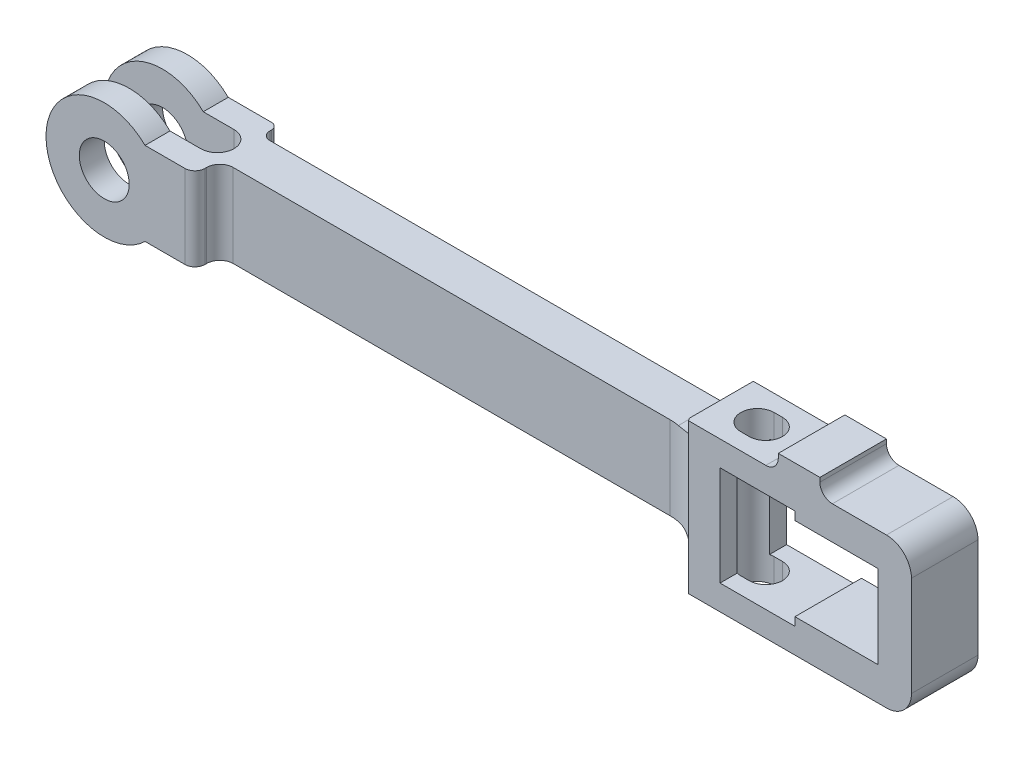
SolidWorks part; units mm, degrees
ref_plane "Plan de face" through (0, 0, 0) normal (0, 0, 1) x (1, 0, 0)
ref_plane "Plan de dessus" through (0, 0, 0) normal (0, 1, 0) x (1, 0, 0)
ref_plane "Plan de droite" through (0, 0, 0) normal (1, 0, 0) x (0, 0, -1)
sketch "Esquisse1" plane through (0, 0, 0) normal (0, 0, 1) x (1, 0, 0)
  line L0 (-1000, 0) -> (49000, 0) construction
  line L1 (3.5, 2.5) -> (2.4495, 2.5)
  line L2 (3.5, -2.5) -> (33.05, -2.5)
  line L6 (3.5, -2.5) -> (2.4495, -2.5)
  line L7 (35, 4.45) -> (35, 4.5)
  line L8 (35, 4.5) -> (39.75, 4.5)
  line L9 (35, -4.45) -> (35, -4.5)
  line L10 (35, -4.5) -> (47, -4.5)
  line L11 (48.5, 3) -> (48.5, -3)
  line L12 (3.5, 2.5) -> (33.05, 2.5)
  line L13 (37, -3) -> (37, 3)
  line L14 (37, 2.5) -> (46.5, 2.5) construction
  line L15 (37, 2.5) -> (37, -2.5) construction
  line L16 (37, -2.5) -> (46.5, -2.5) construction
  line L17 (46.5, 2.5) -> (46.5, -2.5) construction
  line L18 (37, 3) -> (41.5, 3) construction
  line L19 (37, 3) -> (37, -3) construction
  line L20 (37, -3) -> (41.5, -3) construction
  line L21 (41.5, 3) -> (41.5, -3) construction
  line L22 (37, 3) -> (41.5, 3)
  line L23 (41.5, 3) -> (41.5, 2.5)
  line L24 (41.5, 2.5) -> (46.5, 2.5)
  line L25 (46.5, 2.5) -> (46.5, -2.5)
  line L26 (46.5, -2.5) -> (41.5, -2.5)
  line L27 (41.5, -2.5) -> (41.5, -3)
  line L28 (41.5, -3) -> (37, -3)
  line L29 (43.75, 4.5) -> (47, 4.5)
  line L31 (40.5, 5.25) -> (40.5, 5.5)
  line L32 (40.5, 5.5) -> (43, 5.5)
  line L33 (43, 5.25) -> (43, 5.5)
  circle A0 centre (0, 0) radius 1.5
  circle A1 centre (0, 0) radius 3.5
  arc A2 (35, -4.45) -> (33.05, -2.5) centre (33.05, -4.45) ccw
  arc A3 (35, 4.45) -> (33.05, 2.5) centre (33.05, 4.45) cw
  arc A4 (39.75, 4.5) -> (40.5, 5.25) centre (39.75, 5.25) ccw
  arc A5 (43.75, 4.5) -> (43, 5.25) centre (43.75, 5.25) cw
  arc A6 (48.5, 3) -> (47, 4.5) centre (47, 3) ccw
  arc A7 (48.5, -3) -> (47, -4.5) centre (47, -3) cw
  point P34 (43, 5.375)
  point P39 (43, 4.5)
  point P44 (48.5, -4.5)
  dimension "D1" = 3
  dimension "D2" = 7
  dimension "D5" = 1.95
  dimension "D21" = 0.75
  dimension "D23" = 0.75
  dimension "D24" = 1.5
  dimension "D25" = 1.5
  dimension "D3" = 2.5
  dimension "D4" = 37
  dimension "D6" = 46.5
  dimension "D7" = 1.0505
  dimension "D8" = 2.5
  dimension "D9" = 2.5
  dimension "D10" = 13.5
  dimension "D11" = 48.5
  dimension "D12" = 0.05
  dimension "D13" = 5
  dimension "D14" = 6
  dimension "D15" = 3
  dimension "D16" = 41.5
  dimension "D17" = 0
  dimension "D18" = 40.5
  dimension "D19" = 43
  dimension "D20" = 1
  dimension "D22" = 0.25
extrude "Boss.-Extru.1" add sketch "Esquisse1" along normal blind 5 contours A1 A0 | A7 L11 A6 L29 A5 L33 L32 L31 A4 L8 L7 A3 L12 L1 A1 L6 L2 A2 L9 L10 L27 L28 L13 L22 L23 L24 L25 L26
sketch "Esquisse2" plane through (0, 2.5, 0) normal (0, 1, 0) x (1, 0, 0)
  line L0 (-997.5505, -2.5) -> (49002.4495, -2.5) construction
  line L1 (2.4495, -5) -> (2.4495, 0) construction
  line L2 (0, -1000) -> (0, 49000) construction
  line L3 (-997.5505, -3.5) -> (49002.4495, -3.5) construction
  line L4 (3.7273, -3.499) -> (50003.7273, -3.499) construction
  line L5 (-1001.8476, -1) -> (48998.1524, -1) construction
  line L6 (5.9495, -1) -> (48.5, -1)
  line L7 (48.5, -5) -> (48.5, 0) construction
  line L8 (5.4495, -0.5) -> (5.4495, -0.4)
  line L9 (2.4495, 0) -> (33.05, 0) construction
  line L10 (2.4495, 0) -> (5.0495, 0)
  line L11 (-3.5, 0) -> (2.4495, 0)
  line L12 (-3.5, 0) -> (-3.5, -1.5)
  line L13 (-3.5, 0) -> (-3.5, -5) construction
  line L14 (-3.5, -5) -> (-3.5, -3.5)
  line L15 (-3.5, -1.5) -> (3.5, -1.5)
  line L16 (-3.5, -3.5) -> (3.5, -3.5)
  line L17 (2.4495, -5) -> (-3.5, -5)
  line L18 (2.4495, -5) -> (4.8495, -5)
  line L19 (2.4495, -5) -> (33.05, -5) construction
  line L20 (5.4495, -4.4) -> (5.4495, -4.3)
  line L21 (6.2495, -3.5) -> (32.5, -3.5)
  line L22 (32.5, -3.5) -> (32.5, -8.2558) construction
  line L23 (40.5, -5) -> (43, -5) construction
  line L24 (35.0981, -5) -> (48.5, -5)
  line L25 (48.5, -5) -> (48.5, -1)
  line L26 (-3.5, -1.5) -> (-3.5, -3.5)
  line L27 (4.8495, -5) -> (35.0981, -5)
  line L28 (5.0495, 0) -> (48.5, 0)
  line L29 (48.5, 0) -> (48.5, -1)
  line L30 (3.5, -3.5) -> (4.2951, -3.5)
  line L31 (4.2951, -1.5) -> (3.5, -1.5)
  arc A0 (5.9495, -1) -> (5.4495, -0.5) centre (5.9495, -0.5) cw
  arc A1 (5.4495, -0.4) -> (5.0495, 0) centre (5.0495, -0.4) ccw
  arc A3 (5.4495, -4.3) -> (6.2495, -3.5) centre (6.2495, -4.3) cw
  arc A4 (4.8495, -5) -> (5.4495, -4.4) centre (4.8495, -4.4) ccw
  arc A5 (32.5, -3.5) -> (35.0981, -5) centre (32.5, -6.5) cw
  arc A6 (4.2951, -3.5) -> (4.2951, -1.5) centre (4.2951, -2.5) ccw
  point P5 (2.4495, -2.5)
  point P28 (5.4495, 0)
  point P47 (5.4495, -3.5)
  point P50 (5.4495, -5)
  point P51 (32.5, -6.5)
  dimension "D6" = 0.5
  dimension "D7" = 0.4
  dimension "D9" = 1
  dimension "D12" = 0.8
  dimension "D13" = 0.6
  dimension "D1" = 2.5
  dimension "D2" = 1
  dimension "D3" = 1.5
  dimension "D4" = 1.5
  dimension "D5" = 3
  dimension "D8" = 7
  dimension "D10" = 5.4495
  dimension "D11" = 32.5
  dimension "D14" = 3
extrude "Enlèv. mat.-Extru.2" cut sketch "Esquisse2" against normal through all both and the other way through all
sketch "Esquisse3" plane through (0, 4.5, 0) normal (0, 1, 0) x (1, 0, 0)
  line L0 (37.7503, -3) -> (37.2503, -3) construction
  line L1 (37.7503, -4) -> (37.2503, -4)
  line L2 (37.7503, -2) -> (37.2503, -2)
  line L3 (35.0981, -5) -> (39.75, -5) construction
  line L4 (35, -1) -> (39.75, -1) construction
  line L5 (35, -4.8417) -> (35, -1) construction
  arc A0 (37.7503, -4) -> (37.7503, -2) centre (37.7503, -3) ccw
  arc A1 (37.2503, -2) -> (37.2503, -4) centre (37.2503, -3) ccw
  point P0 (38, -3)
  point P4 (37.5003, -3)
  dimension "D3" = 1
  dimension "D5" = 2
  dimension "D1" = 38
  dimension "D2" = 0.5
  dimension "D4" = 1
  dimension "D6" = 3
  dimension "D7" = 0.4997
extrude "Enlèv. mat.-Extru.3" cut sketch "Esquisse3" against normal through all both and the other way through all
